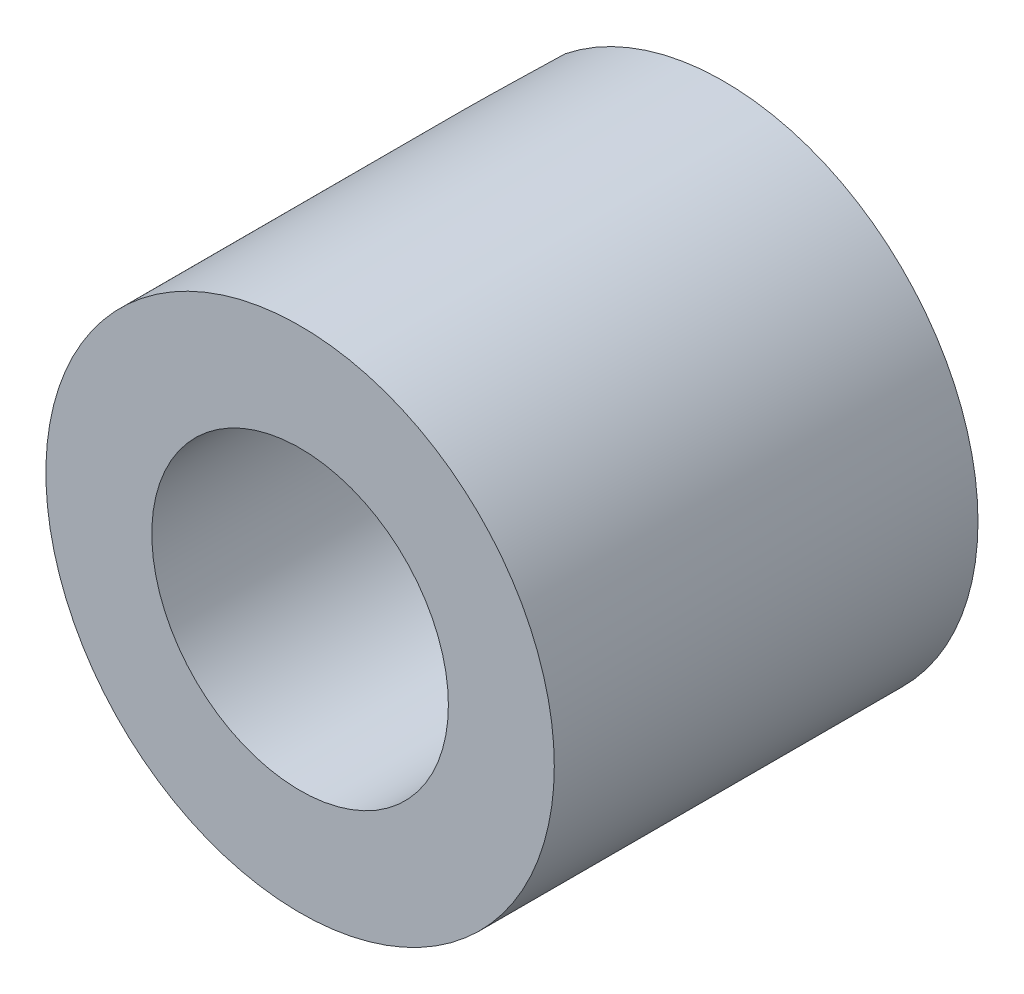
SolidWorks part; units mm, degrees
ref_plane "Face" through (0, 0, 0) normal (0, 0, 1) x (1, 0, 0)
ref_plane "Dessus" through (0, 0, 0) normal (0, 1, 0) x (1, 0, 0)
ref_plane "Droite" through (0, 0, 0) normal (1, 0, 0) x (0, 0, -1)
sketch "Esquisse1" plane through (0, 0, 0) normal (0, 0, 1) x (1, 0, 0)
  circle A0 centre (0, 0) radius 3
  circle A1 centre (0, 0) radius 1.75
  dimension "D1" = 6
  dimension "D2" = 3.5
extrude "Base-Extrusion" add sketch "Esquisse1" along normal blind 5
sketch "Esquisse2" plane through (0, 0, 0) normal (0, 1, 0) x (1, 0, 0)
  circle A0 centre (-8.8, 1) radius 7
  dimension "D1" = 14
  dimension "D2" = 8.8
  dimension "D3" = 1
extrude "Enlèv. mat.-Extru.1" cut sketch "Esquisse2" against normal mid plane 10
